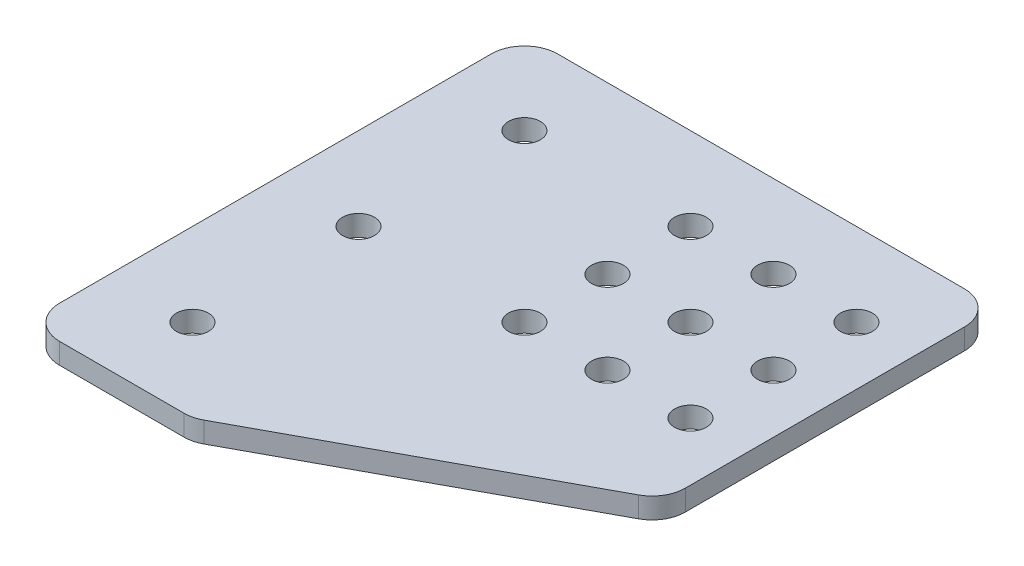
SolidWorks part; units mm, degrees
ref_plane "Front Plane" through (0, 0, 0) normal (0, 0, 1) x (1, 0, 0)
ref_plane "Top Plane" through (0, 0, 0) normal (0, 1, 0) x (1, 0, 0)
ref_plane "Right Plane" through (0, 0, 0) normal (1, 0, 0) x (0, 0, -1)
sketch "Sketch1" plane through (0, 0, 0) normal (0, 1, 0) x (1, 0, 0)
  line L0 (0, -50.8) -> (0, -71.12)
  line L1 (5.08, 0) -> (50.8, 0)
  line L2 (0, -5.08) -> (0, -50.8)
  line L3 (0, -50.8) -> (50.8, -50.8)
  line L4 (50.8, -10.2616) -> (50.8, -15.1384)
  line L5 (50.8, 0) -> (63.5, 0)
  line L6 (50.8, 0) -> (50.8, -50.8)
  line L9 (5.08, -76.2) -> (25.4, -76.2)
  line L10 (50.8, -22.9616) -> (50.8, -27.8384)
  line L11 (0, 0) -> (0, -76.2)
  line L12 (38.1, -38.1) -> (50.8, -38.1) construction
  line L13 (50.8, -25.4) -> (53.2384, -25.4)
  line L14 (63.5, -25.4) -> (63.5, -22.9616)
  line L15 (63.5, -10.2616) -> (63.5, -27.8384)
  line L16 (63.5, -15.1384) -> (63.5, -10.2616)
  line L17 (63.5, 0) -> (72.39, 0)
  line L18 (72.39, 0) -> (72.39, -50.8)
  line L19 (63.5, -35.6616) -> (63.5, -50.8)
  line L20 (50.8, -38.1) -> (63.5, -38.1) construction
  line L21 (25.4, -76.2) -> (72.39, -50.8)
  circle A0 centre (38.1, -12.7) radius 2.4384
  circle A1 centre (38.1, -25.4) radius 2.4384
  circle A2 centre (38.1, -38.1) radius 2.4384
  circle A3 centre (12.7, -12.7) radius 2.4384
  circle A4 centre (12.7, -38.1) radius 2.4384
  circle A8 centre (12.7, -63.5) radius 2.4384
  arc A11 (0, -71.12) -> (5.08, -76.2) centre (5.08, -71.12) ccw
  arc A12 (5.08, 0) -> (0, -5.08) centre (5.08, -5.08) ccw
  circle A13 centre (63.5, -38.1) radius 2.4384
  circle A14 centre (50.8, -38.1) radius 2.4384
  circle A15 centre (50.8, -25.4) radius 2.4384
  circle A16 centre (50.8, -12.7) radius 2.4384
  circle A17 centre (63.5, -12.7) radius 2.4384
  circle A18 centre (63.5, -25.4) radius 2.4384
  point P29 (76.2, 0)
  dimension "D3" = 4.8768
  dimension "D4" = 4.8768
  dimension "D5" = 4.8768
  dimension "D6" = 4.8768
  dimension "D7" = 4.8768
  dimension "D8" = 12.7
  dimension "D9" = 12.7
  dimension "D10" = 38.1
  dimension "D12" = 38.1
  dimension "D13" = 12.7
  dimension "D14" = 12.7
  dimension "D15" = 12.7
  dimension "D16" = 12.7
  dimension "D17" = 25.4
  dimension "D21" = 8.89
  dimension "D22" = 50.8
  dimension "D1" = 50.8
  dimension "D2" = 50.8
  dimension "D11" = 38.1
  dimension "D18" = 25.4
  dimension "D19" = 25.4
  dimension "D20" = 25.4
  dimension "D24" = 12.7
  dimension "D25" = 12.7
  dimension "D26" = 2
  dimension "D27" = 12.7
  dimension "D23" = 2
extrude "Boss-Extrude1" add sketch "Sketch1" along normal blind 3.175
fillet "Fillet3" radius 5.08 3 edges at (25.4, 1.5875, 76.2) (72.39, 1.5875, 0) (72.39, 1.5875, 50.8)
